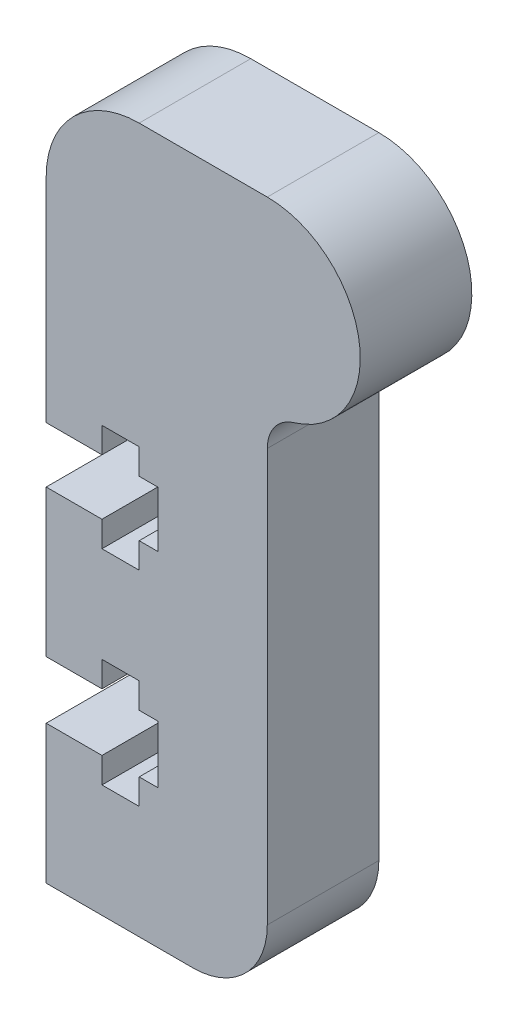
SolidWorks part; units mm, degrees
ref_plane "Płaszczyzna przednia" through (0, 0, 0) normal (0, 0, 1) x (1, 0, 0)
ref_plane "Płaszczyzna górna" through (0, 0, 0) normal (0, 1, 0) x (1, 0, 0)
ref_plane "Płaszczyzna prawa" through (0, 0, 0) normal (1, 0, 0) x (0, 0, -1)
sketch "Szkic2" plane through (0, 0, 0) normal (0, 0, 1) x (1, 0, 0)
  line L2 (7, 97.6955) -> (11.8901, 97.6955) construction
  line L3 (5, 93.6955) -> (11.8893, 93.6955)
  line L58 (3, 61.8721) -> (3, 63.2471)
  line L59 (3, 63.2471) -> (0, 63.2471)
  line L60 (0, 63.2471) -> (0, 55.7971)
  line L61 (0, 55.7971) -> (7.8893, 55.7971)
  line L62 (11.8893, 59.7971) -> (11.8893, 81.9873)
  line L65 (0, 88.6955) -> (0, 77.2455)
  line L66 (0, 77.2455) -> (3, 77.2455)
  line L67 (3, 77.2455) -> (3, 78.6205)
  line L68 (3, 78.6205) -> (5, 78.6205)
  line L69 (5, 78.6205) -> (5, 77.2455)
  line L70 (5, 77.2455) -> (6, 77.2455)
  line L71 (6, 77.2455) -> (6, 74.2471)
  line L72 (6, 74.2471) -> (5, 74.2471)
  line L73 (5, 74.2471) -> (5, 72.8721)
  line L74 (5, 72.8721) -> (3, 72.8721)
  line L75 (3, 72.8721) -> (3, 74.2471)
  line L76 (3, 74.2471) -> (0, 74.2471)
  line L77 (0, 74.2471) -> (0, 66.3471)
  line L78 (0, 66.3471) -> (3, 66.3471)
  line L79 (3, 66.3471) -> (3, 67.7221)
  line L80 (3, 67.7221) -> (5, 67.7221)
  line L81 (5, 67.7221) -> (5, 66.3471)
  line L82 (5, 66.3471) -> (6, 66.3471)
  line L83 (6, 66.3471) -> (6, 63.2471)
  line L84 (6, 63.2471) -> (5, 63.2471)
  line L85 (5, 63.2471) -> (5, 61.8721)
  line L86 (5, 61.8721) -> (3, 61.8721)
  arc A0 (13.3179, 83.9039) -> (11.8893, 93.6955) centre (11.8893, 88.6955) ccw
  arc A1 (11.8893, 81.9873) -> (13.3179, 83.9039) centre (13.8893, 81.9873) cw
  arc A2 (5, 93.6955) -> (0, 88.6955) centre (5, 88.6955) ccw
  arc A8 (7.8893, 55.7971) -> (11.8893, 59.7971) centre (7.8893, 59.7971) ccw
  dimension "D2" = 10
  dimension "D3" = 2
  dimension "D4" = 5
  dimension "D1" = 4
extrude "Dodanie-wyciągnięcie1" add sketch "Szkic2" against normal blind 6
